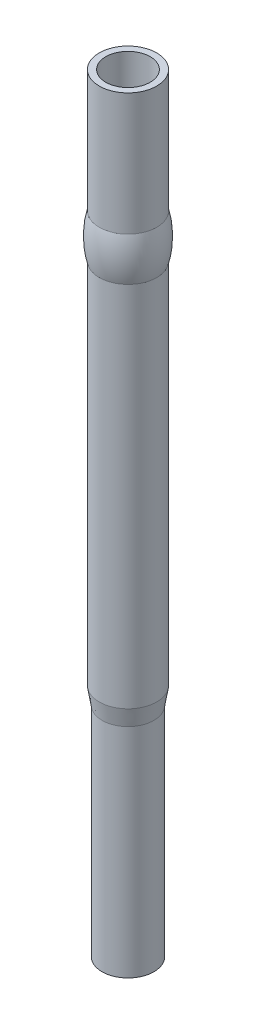
SolidWorks part; units mm, degrees
material "Nickel silver 65-12, UNS C75700"
ref_plane "Front" through (0, 0, 0) normal (0, 0, 1) x (1, 0, 0)
ref_plane "Top" through (0, 0, 0) normal (0, 1, 0) x (1, 0, 0)
ref_plane "Right" through (0, 0, 0) normal (1, 0, 0) x (0, 0, -1)
sketch "Sketch1" plane through (0, 0, 0) normal (1, 0, 0) x (0, 0, -1)
  line L0 (0.51, 0) -> (0.51, -9.9)
  line L1 (0.51, -9.9) -> (0, -9.9)
  line L2 (0, -9.9) -> (0, -12.65)
  line L3 (0, -12.65) -> (0.455, -12.65)
  line L4 (0.455, -12.65) -> (0.455, -17.65)
  line L5 (0.455, -17.65) -> (0.595, -17.65)
  line L6 (0.595, -17.65) -> (0.595, -12.65)
  line L7 (0.595, -12.65) -> (0.66, -12.25)
  line L8 (0.66, -12.25) -> (0.66, -3.81)
  line L9 (0.66, -3.81) -> (0.66, -2.81) construction
  line L10 (0.66, -2.81) -> (0.66, 0)
  line L11 (0.66, 0) -> (0.51, 0)
  arc A0 (0.66, -2.81) -> (0.66, -3.81) centre (-1.2306, -3.31) cw
  point P9 (0.6275, -12.45)
  point P11 (0.725, -3.31)
  dimension "D1" = 0.455
  dimension "D2" = 0.595
  dimension "D3" = 0.66
  dimension "D4" = 0.51
  dimension "D5" = 17.65
  dimension "D6" = 12.45
  dimension "D7" = 0.725
  dimension "D8" = 3.81
  dimension "D9" = 9.9
  dimension "D10" = 5
  dimension "D11" = 1
revolve "Revolve1" add sketch "Sketch1" angle 360 about L2
equation "\"D9@Sketch1\"=17.02-((22.23-17.65)+2.54)"
equation "\"D1@Sketch1\"=0.91/2"
equation "\"D2@Sketch1\"=1.19/2"
equation "\"D7@Sketch1\"=1.45/2"
equation "\"D3@Sketch1\"=1.32/2"
equation "\"D4@Sketch1\"=1.02/2"
